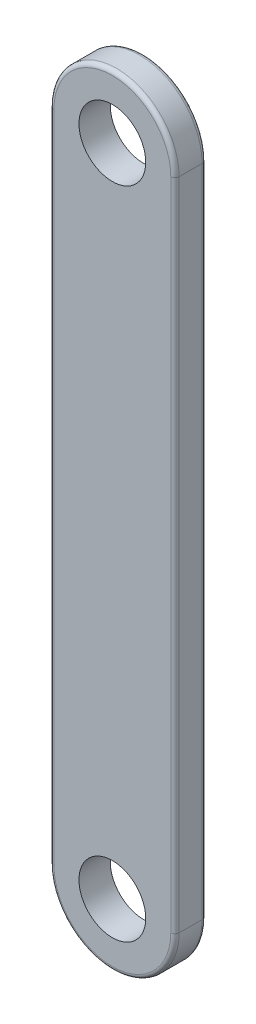
SolidWorks part; units mm, degrees
material "Chrome Stainless Steel"
ref_plane "Front Plane" through (0, 0, 0) normal (0, 0, 1) x (1, 0, 0)
ref_plane "Top Plane" through (0, 0, 0) normal (0, 1, 0) x (1, 0, 0)
ref_plane "Right Plane" through (0, 0, 0) normal (1, 0, 0) x (0, 0, -1)
sketch "Sketch1" plane through (0, 0, 0) normal (0, 0, 1) x (1, 0, 0)
  line L0 (0, 0) -> (0, -41.7404) construction
  line L1 (-3, 0) -> (-3, -31.38)
  line L2 (3, 0) -> (3, -31.38)
  circle A0 centre (0, 0) radius 1.6
  circle A1 centre (0, -31.38) radius 1.6
  arc A2 (3, 0) -> (-3, 0) centre (0, 0) ccw
  arc A3 (-3, -31.38) -> (3, -31.38) centre (0, -31.38) ccw
  dimension "D1" = 3.2
  dimension "D3" = 6
  dimension "D4" = 3.2
  dimension "D2" = 31.38
extrude "Boss-Extrude1" add sketch "Sketch1" along normal blind 1.5
fillet "Fillet1" radius 0.2 8 edges at (0, -34.38, 1.5) (-3, -15.69, 1.5) (0, 3, 1.5) (0, -34.38, 0) (-3, -15.69, 0) (0, 3, 0) (3, -15.69, 1.5) (3, -15.69, 0)
